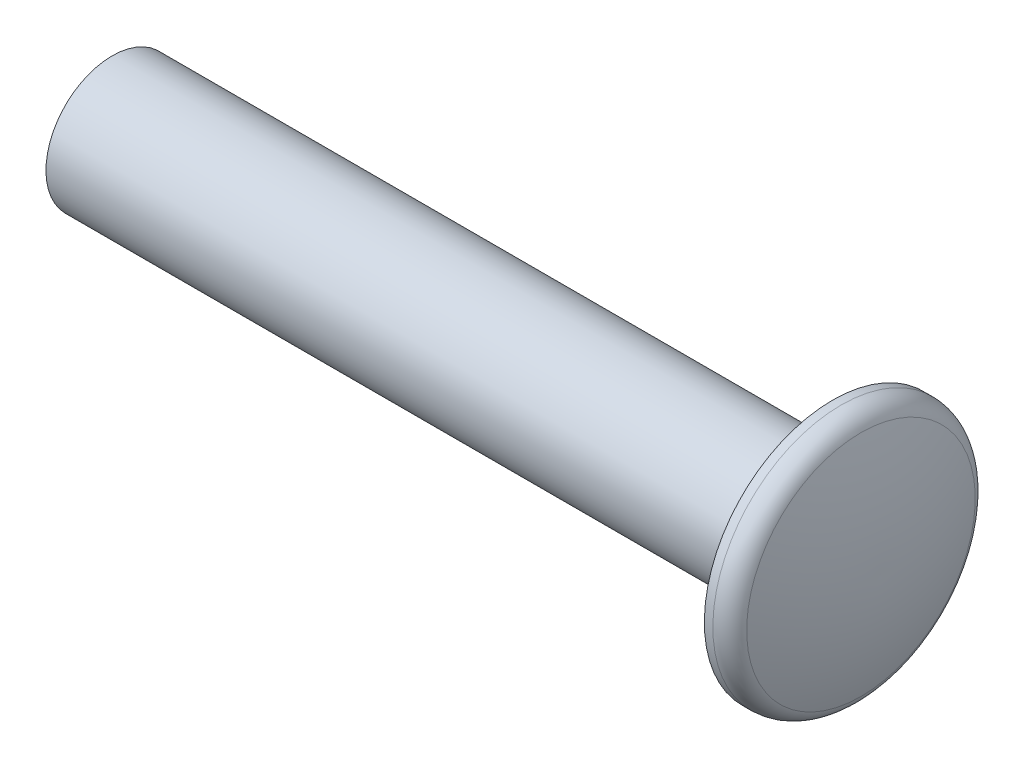
SolidWorks part; units mm, degrees
ref_plane "Front Plane" through (0, 0, 0) normal (0, 0, 1) x (1, 0, 0)
ref_plane "Top Plane" through (0, 0, 0) normal (0, 1, 0) x (1, 0, 0)
ref_plane "Right Plane" through (0, 0, 0) normal (1, 0, 0) x (0, 0, -1)
sketch "Sketch10" plane through (34.2682, 0, 0) normal (0, 0, 1) x (1, 0, 0)
  line L0 (-24.1702, -46.7198) -> (19.0098, -46.7198)
  line L2 (19.0098, -46.7198) -> (19.0098, -50.4358)
  line L5 (-24.1702, -46.7198) -> (-24.1702, -42.751)
  line L6 (21.8673, -42.751) -> (-24.1702, -42.751)
  line L8 (19.0098, -50.4358) -> (19.5197, -50.4358)
  arc A0 (21.8673, -42.751) -> (20.7125, -49.6017) centre (2.8199, -43.0629) cw
  arc A1 (19.5197, -50.4358) -> (20.7125, -49.6017) centre (19.5197, -49.1658) ccw
  point P13 (20.3853, -50.4358)
  dimension "D5" = 19.05
  dimension "D6" = 1.27
  dimension "D1" = 46.0375
  dimension "D2" = 43.18
  dimension "D3" = 3.9624
  dimension "D4" = 3.9688
  dimension "D7" = 10.098
  dimension "D8" = 37.088
revolve "Revolve1" add sketch "Sketch10" angle 360 about L6
